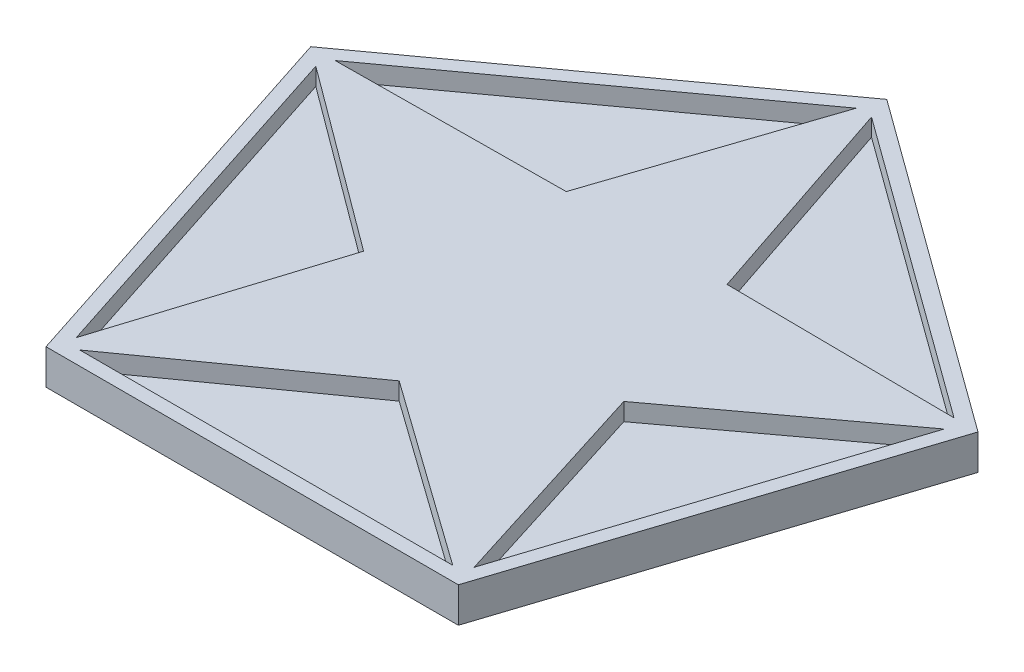
SolidWorks part; units mm, degrees
ref_plane "Front Plane" through (0, 0, 0) normal (0, 0, 1) x (1, 0, 0)
ref_plane "Top Plane" through (0, 0, 0) normal (0, 1, 0) x (1, 0, 0)
ref_plane "Right Plane" through (0, 0, 0) normal (1, 0, 0) x (0, 0, -1)
sketch "Sketch1" plane through (0, 0, 0) normal (0, 1, 0) x (1, 0, 0)
  line L1 (9.5106, 3.0902) -> (0, 10)
  line L2 (0, 10) -> (-9.5106, 3.0902)
  line L3 (-9.5106, 3.0902) -> (-5.8779, -8.0902)
  line L4 (-5.8779, -8.0902) -> (5.8779, -8.0902)
  line L5 (5.8779, -8.0902) -> (9.5106, 3.0902)
  line L6 (5.6707, -7.4334) -> (8.9569, 2.6806)
  line L7 (8.8219, 3.0961) -> (0.2184, 9.3469)
  line L8 (-0.2184, 9.3469) -> (-8.8219, 3.0961)
  line L9 (-8.9569, 2.6806) -> (-5.6707, -7.4334)
  line L10 (-5.3167, -7.6902) -> (5.3172, -7.6902)
  line L12 (-5.6707, -7.4334) -> (-3.7091, -1.2052)
  line L13 (-3.7091, -1.2052) -> (-8.9569, 2.6806)
  line L14 (-8.8219, 3.0961) -> (-2.2924, 3.1552)
  line L15 (-2.2924, 3.1552) -> (-0.2184, 9.3469)
  line L16 (0.2184, 9.3469) -> (2.2924, 3.1552)
  line L17 (2.2924, 3.1552) -> (8.8219, 3.0961)
  line L18 (8.9569, 2.6806) -> (3.7091, -1.2052)
  line L19 (3.7091, -1.2052) -> (5.6707, -7.4334)
  line L21 (-5.3167, -7.6902) -> (0, -3.9)
  line L22 (5.3172, -7.6902) -> (0, -3.9)
  dimension "D2" = 0.4
extrude "Boss-Extrude1" add sketch "Sketch1" along normal blind 1
sketch "Sketch3" plane through (0, 0, 0) normal (0, -1, 0) x (1, 0, 0)
  line L0 (8.9569, -2.6806) -> (3.7091, 1.2052)
  line L1 (3.7091, 1.2052) -> (5.6707, 7.4334)
  line L2 (5.6707, 7.4334) -> (8.9569, -2.6806)
  line L3 (8.8219, -3.0961) -> (2.2924, -3.1552)
  line L4 (2.2924, -3.1552) -> (0.2184, -9.3469)
  line L5 (0.2184, -9.3469) -> (8.8219, -3.0961)
  line L6 (-0.2184, -9.3469) -> (-2.2924, -3.1552)
  line L7 (-2.2924, -3.1552) -> (-8.8219, -3.0961)
  line L8 (-8.8219, -3.0961) -> (-2.2924, -3.1552) construction
  line L9 (-0.2184, -9.3469) -> (-8.8219, -3.0961) construction
  line L10 (-8.8219, -3.0961) -> (-0.2184, -9.3469)
  line L11 (-8.9569, -2.6806) -> (-3.7091, 1.2052)
  line L12 (-3.7091, 1.2052) -> (-5.6707, 7.4334)
  line L13 (-5.6707, 7.4334) -> (-8.9569, -2.6806)
  line L14 (0, 3.9) -> (5.3172, 7.6902)
  line L15 (5.3172, 7.6902) -> (-5.3167, 7.6902)
  line L16 (-5.3167, 7.6902) -> (0, 3.9)
extrude "Boss-Extrude2" add sketch "Sketch3" against normal blind 0.5 separate body
